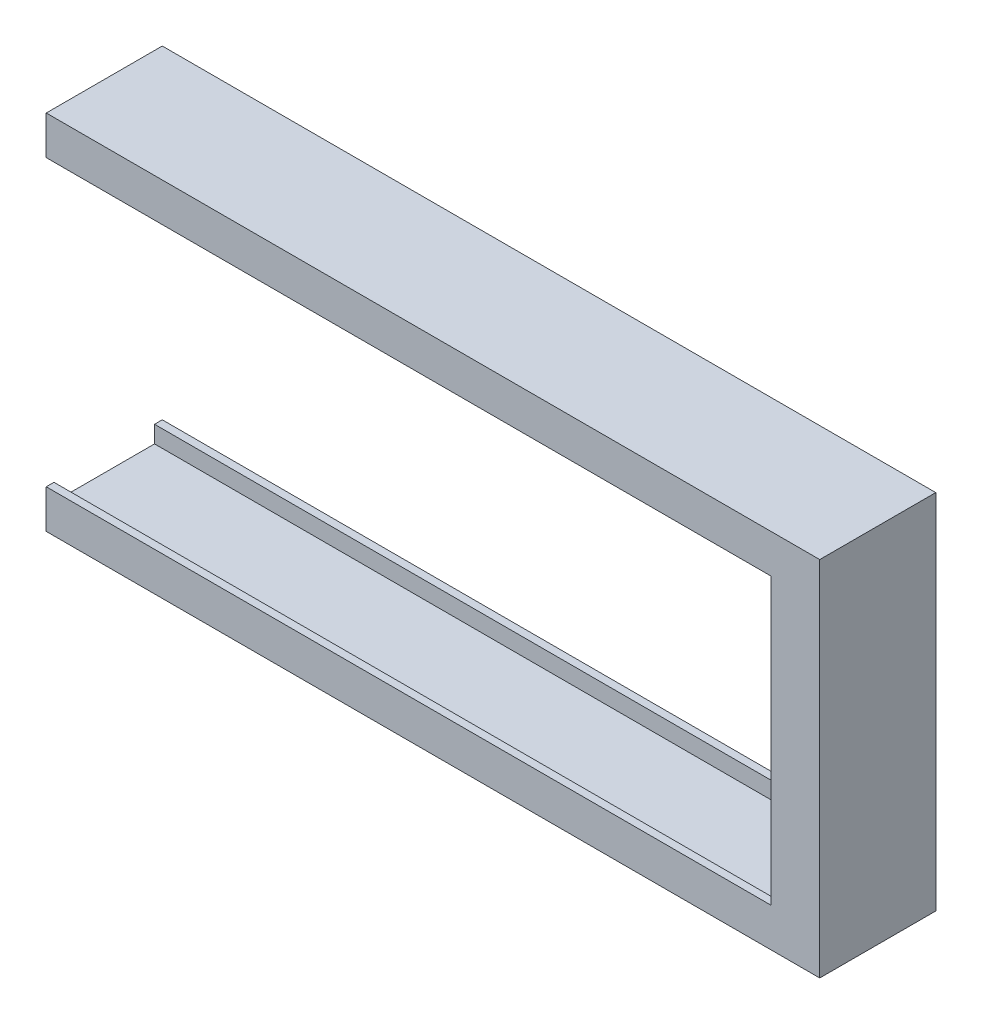
SolidWorks part; units mm, degrees
ref_plane "Front Plane" through (0, 0, 0) normal (0, 0, 1) x (1, 0, 0)
ref_plane "Top Plane" through (0, 0, 0) normal (0, 1, 0) x (1, 0, 0)
ref_plane "Right Plane" through (0, 0, 0) normal (1, 0, 0) x (0, 0, -1)
sketch "Sketch1" plane through (0, 0, 0) normal (0, 0, 1) x (1, 0, 0)
  line L1 (-127, -59.4995) -> (127, -59.4995)
  line L2 (-127, -59.4995) -> (-127, 59.4995)
  line L3 (-127, 59.4995) -> (127, 59.4995)
  line L4 (127, -59.4995) -> (127, 59.4995)
  line L5 (-127, -59.4995) -> (127, 59.4995) construction
  line L6 (-127, 59.4995) -> (127, -59.4995) construction
  point P0 (0, 0)
extrude "Boss-Extrude1" add sketch "Sketch1" against normal blind 38.1
sketch "Sketch2" plane through (-127, 0, 0) normal (-1, 0, 0) x (0, 0, 1)
  line L4 (-2.54, 52.3875) -> (-2.54, -52.3875)
  line L5 (-35.56, 52.3875) -> (-2.54, -52.3875) construction
  line L6 (-35.56, -49.0855) -> (-2.54, 52.3875) construction
  line L7 (-38.1, 59.4995) -> (-38.1, -59.4995) construction
  line L8 (0, 59.4995) -> (0, -59.4995) construction
  line L10 (-35.56, 52.3875) -> (-2.54, 52.3875)
  line L12 (-38.1, -59.4995) -> (0, -59.4995) construction
  line L14 (-35.56, 52.3875) -> (-35.56, -52.3875)
  line L15 (-35.56, -52.3875) -> (-2.54, -52.3875)
  point P0 (-19.3143, 0.8387)
  point P1 (0, 0)
  point P11 (0, 0)
  point P13 (0, 0)
  point P14 (0, 0)
  point P15 (0, 0)
  point P16 (0, 0)
  point P17 (0, 0)
  dimension "D1" = 2.54
  dimension "D2" = 2.54
  dimension "D3" = 7.112
  dimension "D4" = 7.112
  dimension "D5" = 104.775
extrude "Cut-Extrude1" cut sketch "Sketch2" against normal blind 241.3
sketch "Sketch5" plane through (0, 0, 0) normal (0, 0, 1) x (1, 0, 0)
  line L1 (-127, 46.7995) -> (-127, -46.7995)
  line L5 (-127, 59.4995) -> (-127, -59.4995) construction
  line L11 (111.0173, 46.7995) -> (111.0173, -46.7995)
  line L12 (111.0173, 46.7995) -> (-127, 46.7995)
  line L13 (111.0173, -46.7995) -> (-127, -46.7995)
  dimension "D1" = 12.7
  dimension "D2" = 12.7
extrude "Cut-Extrude2" cut sketch "Sketch5" against normal blind 38.354
